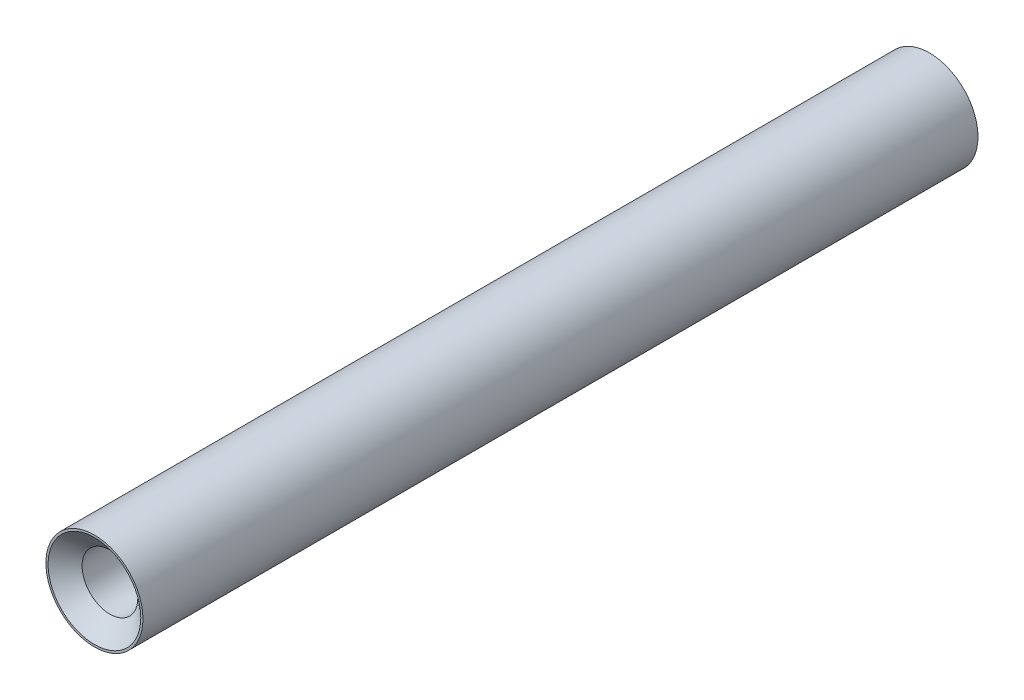
SolidWorks part; units mm, degrees
ref_plane "Ön Düzlem" through (0, 0, 0) normal (0, 0, 1) x (1, 0, 0)
ref_plane "Üst Düzlem" through (0, 0, 0) normal (0, 1, 0) x (1, 0, 0)
ref_plane "Sağ Düzlem" through (0, 0, 0) normal (1, 0, 0) x (0, 0, -1)
sketch "Sketch1" plane through (0, 0, 0) normal (0, 0, 1) x (1, 0, 0)
  circle A0 centre (0, 0) radius 2.5
  dimension "D1" = 5
extrude "Boss-Extrude1" add sketch "Sketch1" along normal blind 43.02
hole_wizard "#6-40 Tapped Hole1" positions "3DSketch2" profile "Sketch3" tap size "#6-40" standard "ANSI Inch"
sketch3d "3DSketch2"
  line L0 (0, 0, 43.02) -> (0, 0, 0) construction
  point P0 (0, 0, 43.02)
sketch "Sketch3" plane through (0, 0, 43.02) normal (1, 0, 0) x (0, -1, 0)
  line L0 (0, 0) -> (0, 9.7823)
  line L1 (0, 9.7823) -> (1.4351, 8.92)
  line L2 (1.4351, 8.92) -> (1.4351, 0.7992)
  line L3 (1.4351, 0.7992) -> (2.3876, 0)
  line L5 (2.3876, 0) -> (0, 0)
  line L6 (-1.4351, 0.7992) -> (-2.3876, 0) construction
  line L10 (0, 9.7823) -> (-1.4351, 8.92) construction
  line L11 (0, -6.35) -> (0, 107.95) construction
  dimension "Tap Drill Dia." = 2.8702
  dimension "Tap Drill Depth" = 8.92
  dimension "Near C'Sink Dia." = 4.7752
  dimension "Near C'Sink Angle" = 100
  dimension "Drill Angle" = 118
cosmetic thread "Hole Thread1" parameters "D1"=7.01, "D2"=3.5052
ref_plane "Plane1" through (0, 0, 21.51) normal (0, 0, 1) x (1, 0, 0)
mirror "Mirror1" about plane through (0, 0, 21.51) normal (0, 0, 1) of "#6-40 Tapped Hole1"
